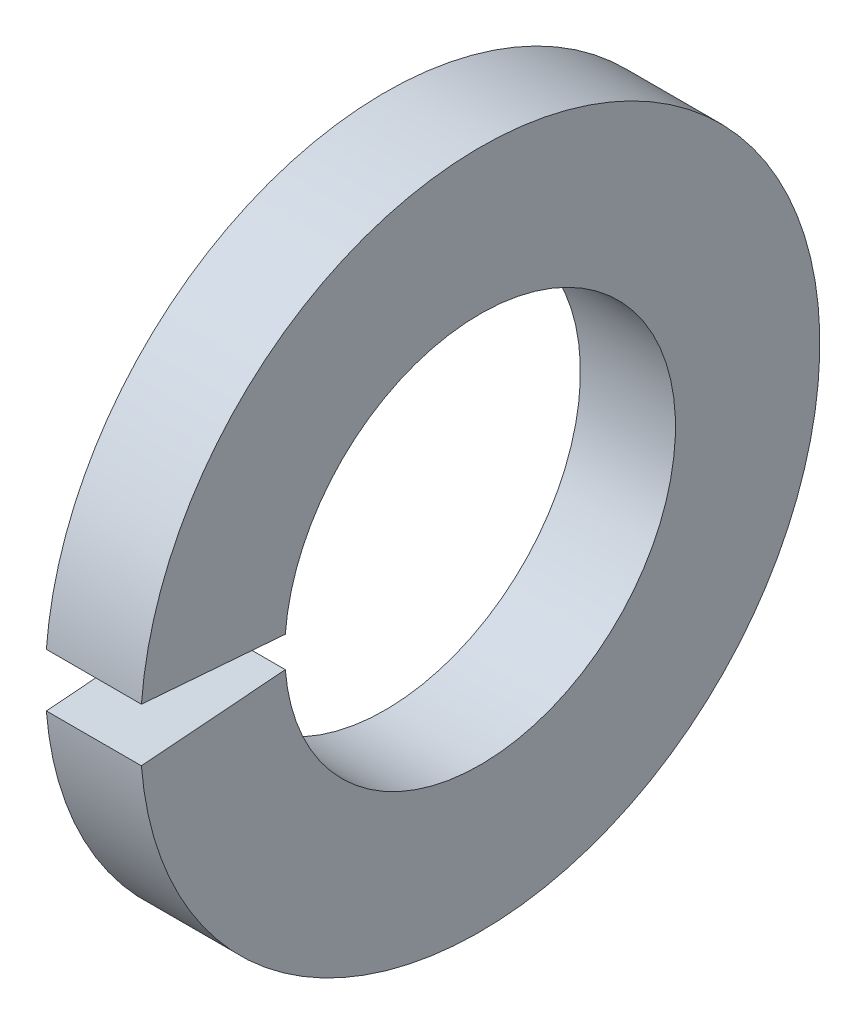
SolidWorks part; units mm, degrees
ref_plane "Plane1" through (0, 0, 0) normal (0, 0, 1) x (1, 0, 0)
ref_plane "Plane2" through (0, 0, 0) normal (0, 1, 0) x (1, 0, 0)
ref_plane "Plane3" through (0, 0, 0) normal (1, 0, 0) x (0, 0, -1)
sketch "Sketch1" plane through (0, 0, 0) normal (0, 0, 1) x (1, 0, 0)
  line L0 (-34.925, 0) -> (9.525, 0) construction
  line L1 (0, 5.6896) -> (0, 9.8933)
  line L2 (0, 9.8933) -> (-2.7686, 9.8933)
  line L3 (-2.7686, 9.8933) -> (-2.7686, 5.6896)
  line L4 (-2.7686, 5.6896) -> (0, 5.6896)
  dimension "Thickness" = 2.7686
  dimension "Inside_dia" = 11.3792
  dimension "Outside_dia" = 19.7866
revolve "Base-Revolve" add sketch "Sketch1" angle 360 about L0
sketch "Sketch2" plane through (0, 0, 0) normal (-1, 0, 0) x (0, -1, 0)
  line L0 (0, 0) -> (0.7917, 10.0601)
  line L1 (0, -3.175) -> (0, 12.7) construction
  line L2 (0, 0) -> (-0.7917, 10.0601)
  arc A0 (0.7917, 10.0601) -> (-0.7917, 10.0601) centre (0, 0) ccw
  dimension "Gap_ang" = 9
  dimension "D1" = 10.0912
extrude "Gap" cut sketch "Sketch2" along normal through all
equation "\"D1@Sketch2\" = \"Outside_dia@Sketch1\" * 0.51"
